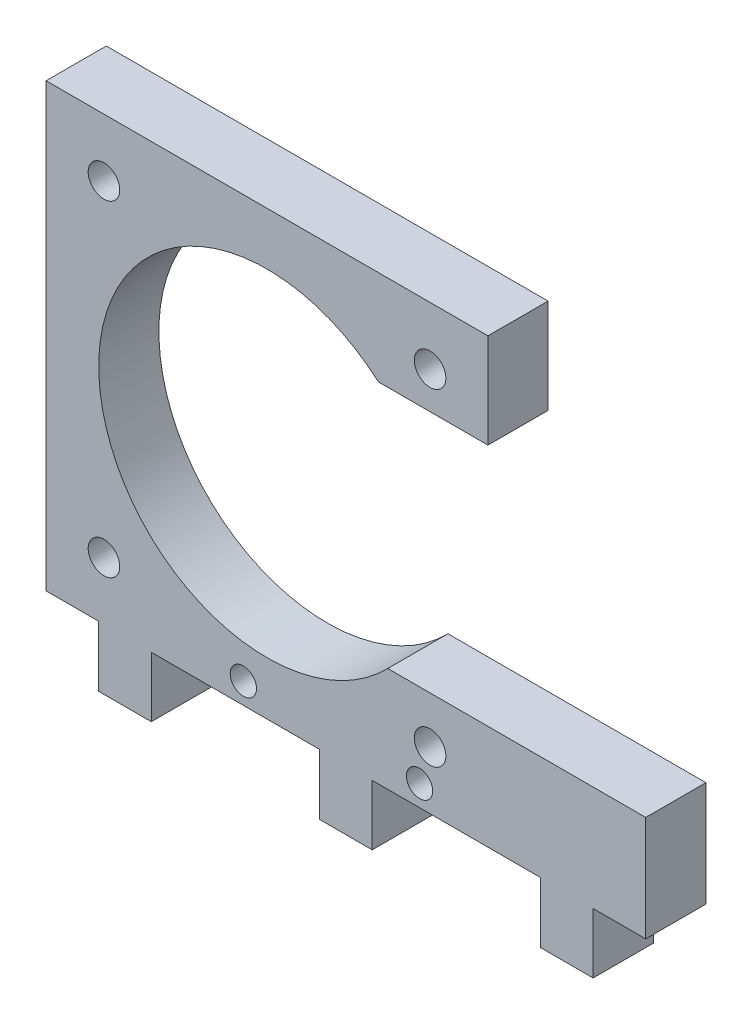
SolidWorks part; units mm, degrees
ref_plane "Front Plane" through (0, 0, 0) normal (0, 0, 1) x (1, 0, 0)
ref_plane "Top Plane" through (0, 0, 0) normal (0, 1, 0) x (1, 0, 0)
ref_plane "Right Plane" through (0, 0, 0) normal (1, 0, 0) x (0, 0, -1)
sketch "Sketch1" plane through (0, 0, 0) normal (0, 0, 1) x (1, 0, 0)
  line L0 (9.38, 23.1479) -> (-1.037, 23.1479)
  line L1 (24.38, 0) -> (24.38, -10)
  line L2 (24.38, -10) -> (19.38, -10)
  line L3 (19.38, -10) -> (19.38, -15.72)
  line L4 (19.38, -15.72) -> (14.38, -15.72)
  line L5 (14.38, -15.72) -> (14.38, -9.9507)
  line L6 (14.38, -9.9507) -> (-1.62, -9.9507)
  line L7 (-1.62, -9.9507) -> (-1.62, -15.6707)
  line L8 (-1.62, -15.6707) -> (-6.62, -15.6707)
  line L9 (-6.62, -15.6707) -> (-6.62, -9.9014)
  line L10 (-6.62, -9.9014) -> (-22.62, -9.9014)
  line L11 (-22.62, -9.9014) -> (-22.62, -15.6214)
  line L12 (-22.62, -15.6214) -> (-27.62, -15.6214)
  line L13 (-27.62, -15.6214) -> (-27.62, -9.8521)
  line L14 (-27.62, -9.8521) -> (-32.62, -9.8521)
  line L15 (-32.62, -9.8521) -> (-32.62, 32.1479)
  line L16 (-32.62, 32.1479) -> (9.38, 32.1479)
  line L17 (9.38, 32.1479) -> (9.38, 23.1479)
  line L18 (24.38, 0) -> (-0.1429, 0)
  arc A0 (-1.037, 23.1479) -> (-0.1429, 0) centre (-11.62, 11.1479) ccw
  circle A1 centre (2.88, -7.9507) radius 1.25
  circle A2 centre (-13.87, -7.9014) radius 1.25
  circle A3 centre (3.8798, -4.4507) radius 1.5
  circle A4 centre (-27.12, -4.3521) radius 1.5
  circle A5 centre (-27.12, 26.6479) radius 1.5
  circle A6 centre (3.88, 26.6479) radius 1.5
  dimension "D17" = 21
  dimension "D18" = 21
  dimension "D19" = 3
  dimension "D20" = 2.5
  dimension "D21" = 2.5
  dimension "D23" = 2
  dimension "D24" = 4.5
  dimension "D25" = 7.25
  dimension "D14" = 32
  dimension "D26" = 3
  dimension "D27" = 3
  dimension "D28" = 3
  dimension "D29" = 5.5
  dimension "D30" = 5.5
  dimension "D31" = 5.5
  dimension "D32" = 5.5
  dimension "D33" = 5.5
  dimension "D35" = 5.5
  dimension "D36" = 5.5
  dimension "D2" = 10
  dimension "D3" = 5
  dimension "D4" = 16
  dimension "D5" = 16
  dimension "D6" = 5
  dimension "D7" = 5
  dimension "D8" = 5
  dimension "D9" = 5
  dimension "D10" = 5.72
  dimension "D11" = 5.72
  dimension "D12" = 5.72
  dimension "D13" = 42
  dimension "D15" = 42
  dimension "D16" = 9
  dimension "D22" = 2
  dimension "D34" = 31
extrude "Boss-Extrude1" add sketch "Sketch1" along normal blind 5.72
